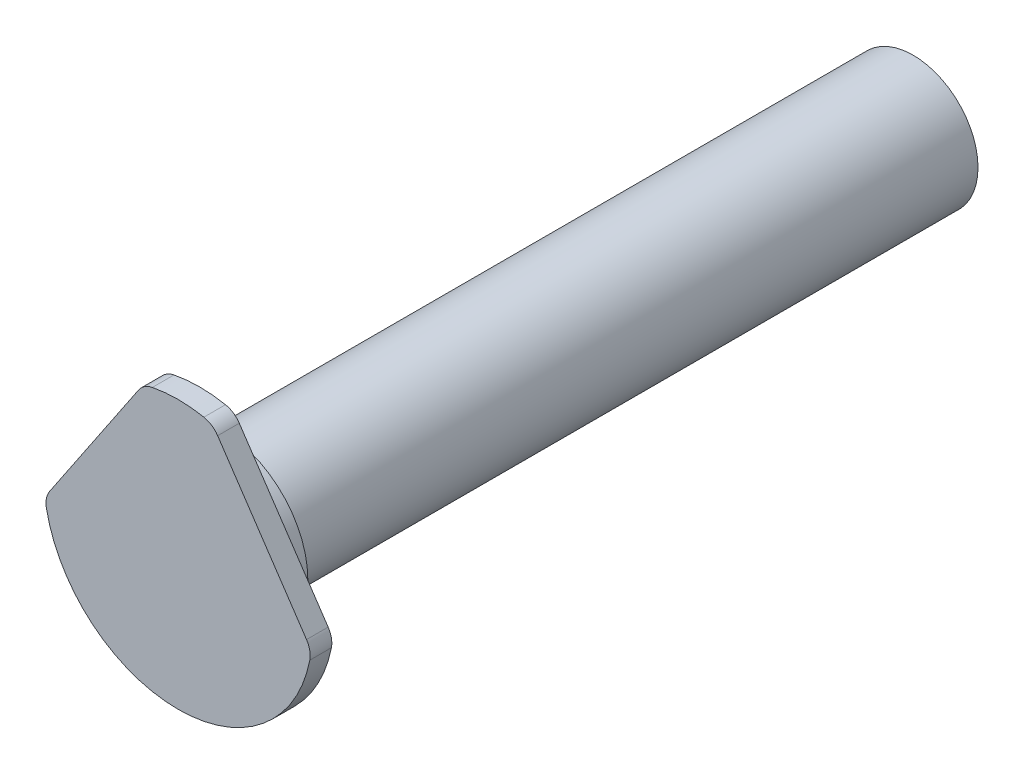
SolidWorks part; units mm, degrees
ref_plane "前基準面" through (0, 0, 0) normal (0, 0, 1) x (1, 0, 0)
ref_plane "上基準面" through (0, 0, 0) normal (0, 1, 0) x (1, 0, 0)
ref_plane "右基準面" through (0, 0, 0) normal (1, 0, 0) x (0, 0, -1)
sketch "草圖1" plane through (0, 0, 0) normal (0, 0, 1) x (1, 0, 0)
  circle A0 centre (0, 0) radius 1.5
  dimension "D1" = 3
extrude "填料-伸長1" add sketch "草圖1" against normal blind 16
sketch "草圖2" plane through (0, 0, 0) normal (0, 0, 1) x (1, 0, 0)
  circle A0 centre (0, 0) radius 2
  dimension "D1" = 4
extrude "填料-伸長2" add sketch "草圖2" along normal blind 0.5
sketch "草圖3" plane through (0, 0, 0.5) normal (0, 0, 1) x (1, 0, 0)
  line L0 (-2.5554, 0) -> (-2, 0)
  line L1 (-1, 1) -> (-1, 2.5554)
  line L2 (0, 0) -> (0, 3.7037) construction
  line L3 (1, 1) -> (1, 2.5554)
  line L4 (2, 0) -> (2.5554, 0)
  line L5 (-0.9149, 2.8345) -> (-2.9703, -0.2209)
  line L6 (0.9149, 2.8345) -> (2.9703, -0.2209)
  arc A0 (-3.0461, -0.596) -> (3.0461, -0.596) centre (0, 0) ccw
  arc A1 (0.596, 3.0461) -> (-0.596, 3.0461) centre (0, 0) ccw
  arc A2 (1, 2.5554) -> (0.596, 3.0461) centre (0.5, 2.5554) ccw
  arc A3 (-1, 2.5554) -> (-0.596, 3.0461) centre (-0.5, 2.5554) cw
  arc A4 (-2.5554, 0) -> (-3.0461, -0.596) centre (-2.5554, -0.5) ccw
  arc A5 (3.0461, -0.596) -> (2.5554, 0) centre (2.5554, -0.5) ccw
  arc A6 (1, 1) -> (2, 0) centre (2, 1) ccw
  arc A7 (-1, 1) -> (-2, 0) centre (-2, 1) cw
  point P11 (1, 2.9384)
  point P14 (-1, 2.9384)
  point P17 (-3.1039, 0)
  point P20 (3.1039, 0)
  point P23 (1, 0)
  point P26 (-1, 0)
  dimension "D1" = 0.5
  dimension "D2" = 0.5
  dimension "D3" = 1
  dimension "D5" = 3.1039
  dimension "D4" = 2
extrude "填料-伸長3" add sketch "草圖3" along normal blind 0.5
sketch "草圖4" plane through (0, 0, 1) normal (0, 0, 1) x (1, 0, 0)
  circle A0 centre (0, 0) radius 2.275
  dimension "D1" = 4.55
